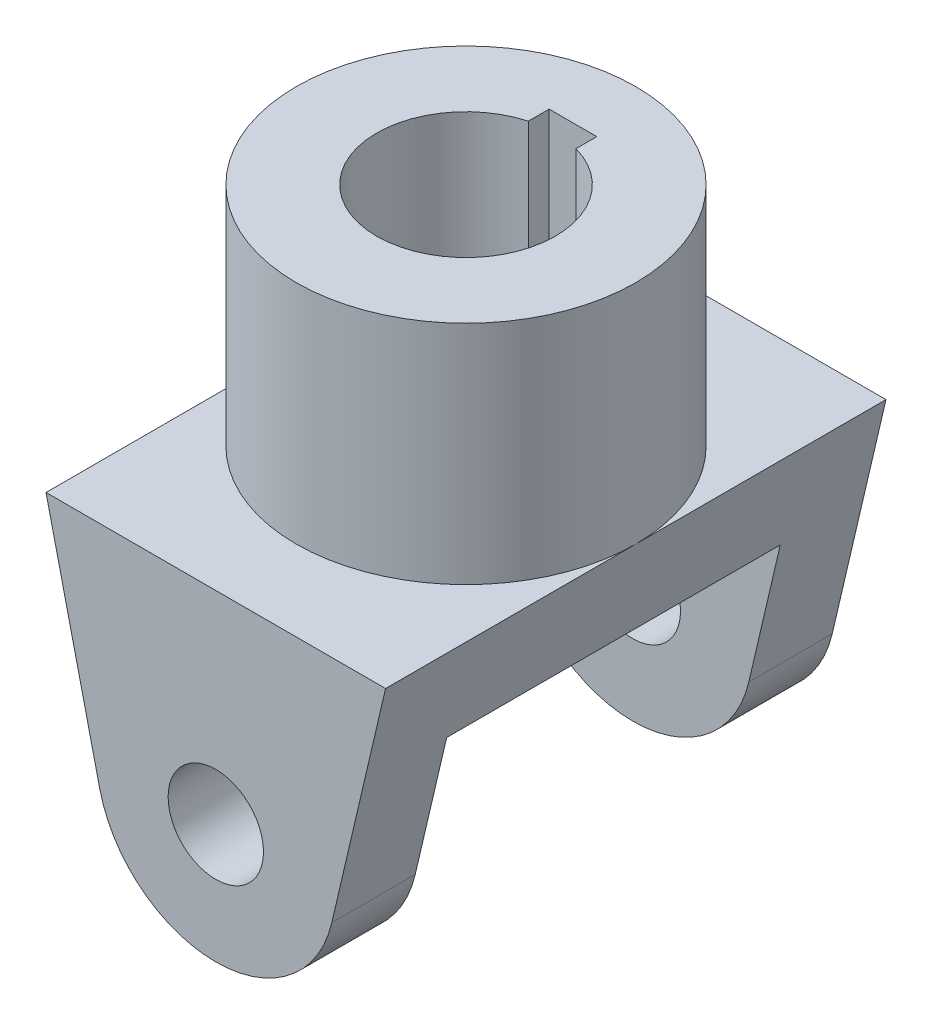
SolidWorks part; units mm, degrees
material "Cast Carbon Steel"
ref_plane "Front Plane" through (0, 0, 0) normal (0, 0, 1) x (1, 0, 0)
ref_plane "Top Plane" through (0, 0, 0) normal (0, 1, 0) x (1, 0, 0)
ref_plane "Right Plane" through (0, 0, 0) normal (1, 0, 0) x (0, 0, -1)
sketch "Sketch1" plane through (0, 0, 0) normal (0, 1, 0) x (1, 0, 0)
  circle A0 centre (0, 0) radius 28.5
  circle A1 centre (0, 0) radius 15
  dimension "D1" = 30
  dimension "D2" = 57
extrude "Boss-Extrude1" add sketch "Sketch1" along normal blind 38
sketch "Sketch2" plane through (0, 0, 0) normal (0, -1, 0) x (1, 0, 0)
  line L1 (28.5, 42) -> (-28.5, 42)
  line L2 (28.5, 42) -> (28.5, -42)
  line L3 (28.5, -42) -> (-28.5, -42)
  line L4 (-28.5, 42) -> (-28.5, -42)
  line L5 (28.5, 42) -> (-28.5, -42) construction
  line L6 (28.5, -42) -> (-28.5, 42) construction
  point P0 (0, 0)
extrude "Boss-Extrude2" add sketch "Sketch2" along normal blind 16
sketch "Sketch6" plane through (0, 0, 42) normal (0, 0, 1) x (1, 0, 0)
  line L1 (-28.5, -16) -> (28.5, -16)
  line L2 (-28.5, -16) -> (-28.5, -54)
  line L3 (-28.5, -54) -> (28.5, -54)
  line L4 (28.5, -16) -> (28.5, -54)
extrude "Boss-Extrude4" add sketch "Sketch6" against normal blind 14
ref_plane "Plane2" through (0, 0, 0) normal (0, 0, 1) x (1, 0, 0)
sketch "Sketch7" plane through (0, 0, -42) normal (0, 0, -1) x (-1, 0, 0)
  line L1 (-28.5, -16) -> (28.5, -16)
  line L2 (-28.5, -16) -> (-28.5, -54)
  line L3 (-28.5, -54) -> (28.5, -54)
  line L4 (28.5, -16) -> (28.5, -54)
extrude "Boss-Extrude5" add sketch "Sketch7" against normal blind 14
sketch "Sketch8" plane through (0, 0, -42) normal (0, 0, -1) x (-1, 0, 0)
  line L0 (0, 38) -> (0, -34) construction
  line L1 (28.5, 38) -> (-28.5, 38) construction
  line L2 (28.5, 0) -> (-28.5, 0) construction
  circle A0 centre (0, -34) radius 8
  dimension "D1" = 34
extrude "Cut-Extrude3" cut sketch "Sketch8" against normal through all
sketch "Sketch9" plane through (0, 0, 42) normal (0, 0, 1) x (1, 0, 0)
  line L0 (-28.5, 0) -> (-19.4735, -38.5587)
  line L2 (28.5, 0) -> (19.4735, -38.5587)
  line L3 (-28.5, 0) -> (-28.5, -54)
  line L4 (-28.5, -54) -> (28.5, -54)
  line L5 (28.5, -54) -> (28.5, 0)
  arc A0 (-19.4735, -38.5587) -> (19.4735, -38.5587) centre (0, -34) ccw
  line M3 (-28.5, 0) -> (-28.5, -54)
  line M4 (-28.5, -54) -> (28.5, -54)
  line M5 (28.5, -54) -> (28.5, 0)
extrude "Cut-Extrude4" cut sketch "Sketch9" against normal through all contours A0 L0 M3 M4 | A0 L4 L2 M5
sketch "Sketch10" plane through (0, 38, 0) normal (0, 1, 0) x (1, 0, 0)
  line L0 (0, 15) -> (0, 0) construction
  circle A0 centre (0, 0) radius 15 construction
  circle A1 centre (0, 0) radius 15 construction
ref_plane "Plane3" through (0, 38, -15) normal (0, 0, 1) x (1, 0, 0)
sketch "Sketch11" plane through (0, 38, 0) normal (0, 1, 0) x (1, 0, 0)
  line L1 (-4, 17.9568) -> (4, 17.9568)
  line L2 (-4, 17.9568) -> (-4, 14.4568)
  line L3 (4, 17.9568) -> (4, 14.4568)
  line L6 (0, 15) -> (0, 17.9568) construction
  arc A0 (4, 14.4568) -> (-4, 14.4568) centre (0, 0) ccw
  circle A1 centre (0, 0) radius 15 construction
  dimension "D1" = 3.5
extrude "Cut-Extrude5" cut sketch "Sketch11" against normal blind 38
scale "Escala1" scale about centroid uniform scaling yes scale factor 0.5
